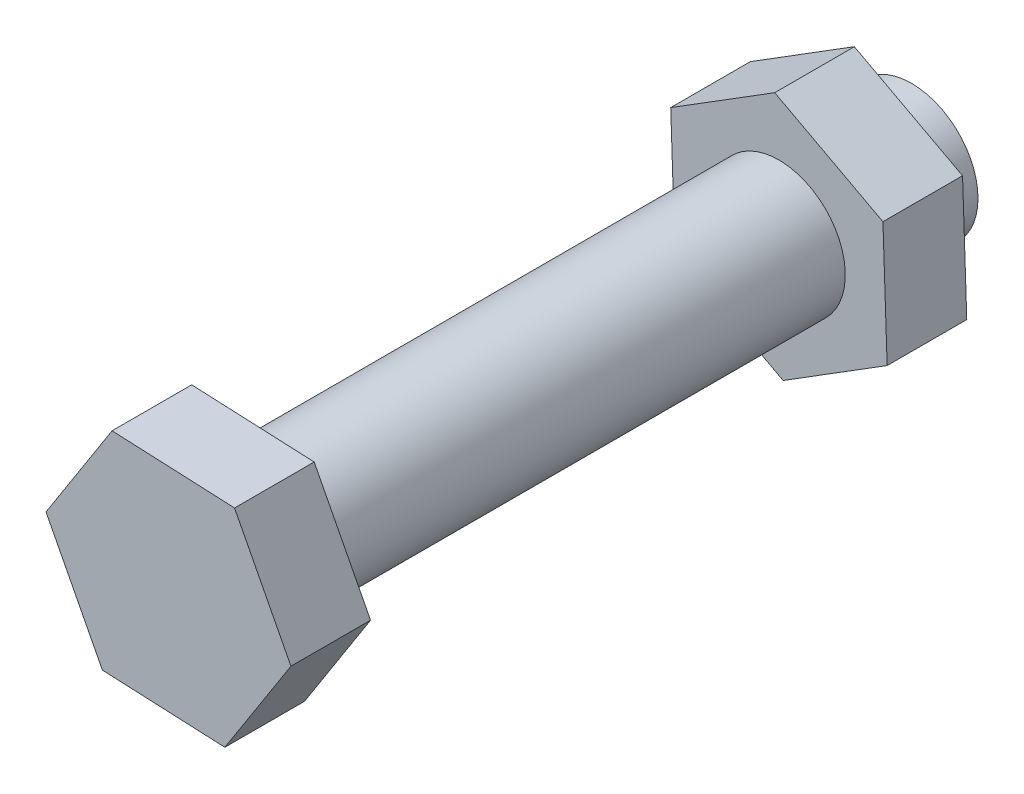
SolidWorks part; units mm, degrees
ref_plane "Front Plane" through (0, 0, 0) normal (0, 0, 1) x (1, 0, 0)
ref_plane "Top Plane" through (0, 0, 0) normal (0, 1, 0) x (1, 0, 0)
ref_plane "Right Plane" through (0, 0, 0) normal (1, 0, 0) x (0, 0, -1)
sketch "Sketch1" plane through (0, 0, 0) normal (0, 0, 1) x (1, 0, 0)
  circle A0 centre (0, 0) radius 2.5
extrude "Boss-Extrude1" add sketch "Sketch1" along normal blind 23
sketch "Sketch2" plane through (0, 0, 23) normal (0, 0, 1) x (1, 0, 0)
  line L1 (2.4895, 3.8905) -> (-2.1245, 4.1012)
  line L2 (-2.1245, 4.1012) -> (-4.614, 0.2107)
  line L3 (-4.614, 0.2107) -> (-2.4895, -3.8905)
  line L4 (-2.4895, -3.8905) -> (2.1245, -4.1012)
  line L5 (2.1245, -4.1012) -> (4.614, -0.2107)
  line L6 (4.614, -0.2107) -> (2.4895, 3.8905)
  circle A0 centre (0, 0) radius 4 construction
  dimension "D1" = 8
extrude "Boss-Extrude2" add sketch "Sketch2" along normal blind 3
sketch "Sketch3" plane through (0, 0, 0) normal (0, 0, -1) x (-1, 0, 0)
  line L1 (4.0771, 2.1704) -> (0.1589, 4.6161)
  line L2 (0.1589, 4.6161) -> (-3.9182, 2.4456)
  line L3 (-3.9182, 2.4456) -> (-4.0771, -2.1704)
  line L4 (-4.0771, -2.1704) -> (-0.1589, -4.6161)
  line L5 (-0.1589, -4.6161) -> (3.9182, -2.4456)
  line L6 (3.9182, -2.4456) -> (4.0771, 2.1704)
  circle A0 centre (0, 0) radius 4 construction
  dimension "D1" = 8
extrude "Boss-Extrude3" add sketch "Sketch3" against normal blind 3
sketch "Sketch4" plane through (0, 0, 0) normal (0, 0, -1) x (-1, 0, 0)
  circle A0 centre (0, 0) radius 2.5
extrude "Boss-Extrude4" add sketch "Sketch4" along normal blind 2
